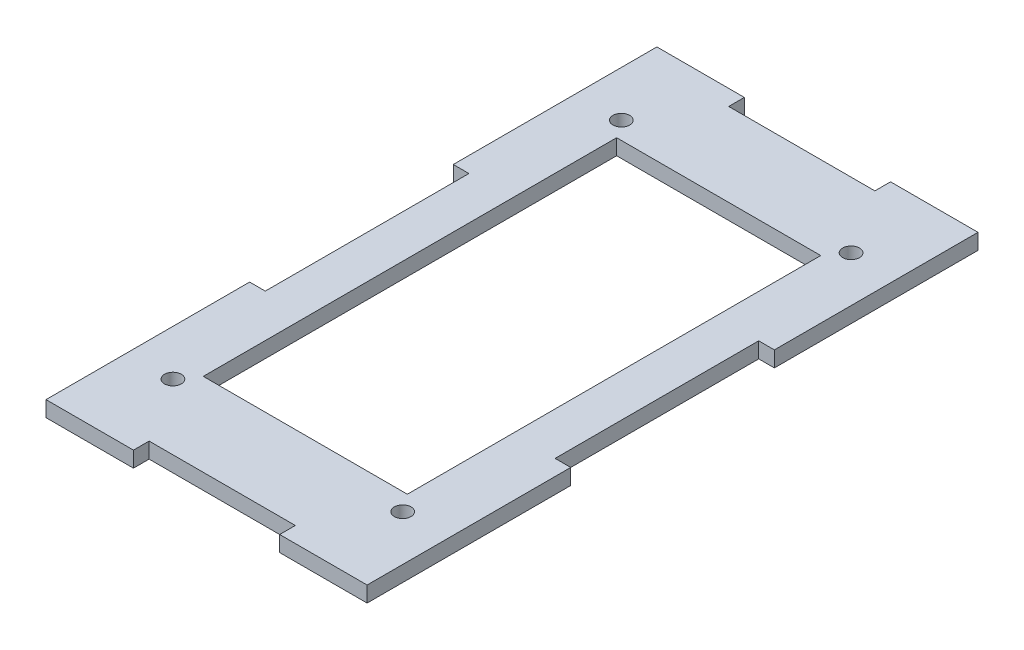
SolidWorks part; units mm, degrees
ref_plane "Front Plane" through (0, 0, 0) normal (0, 0, 1) x (1, 0, 0)
ref_plane "Top Plane" through (0, 0, 0) normal (0, 1, 0) x (1, 0, 0)
ref_plane "Right Plane" through (0, 0, 0) normal (1, 0, 0) x (0, 0, -1)
sketch "Sketch1" plane through (0, 0, 0) normal (0, 1, 0) x (1, 0, 0)
  line L0 (-30.75, 58.5) -> (-30.75, 19.5)
  line L1 (-30.75, -58.5) -> (30.75, -58.5) construction
  line L2 (-30.75, -58.5) -> (-30.75, 58.5) construction
  line L3 (-30.75, 58.5) -> (30.75, 58.5) construction
  line L4 (30.75, -58.5) -> (30.75, 58.5) construction
  line L5 (-30.75, -58.5) -> (30.75, 58.5) construction
  line L6 (-30.75, 58.5) -> (30.75, -58.5) construction
  line L7 (-27.75, -55.5) -> (27.75, -55.5) construction
  line L8 (-27.75, -55.5) -> (-27.75, 55.5) construction
  line L9 (-27.75, 55.5) -> (27.75, 55.5) construction
  line L10 (27.75, -55.5) -> (27.75, 55.5) construction
  line L11 (-27.75, -55.5) -> (27.75, 55.5) construction
  line L12 (-27.75, 55.5) -> (27.75, -55.5) construction
  line L13 (-30.75, 19.5) -> (-27.75, 19.5)
  line L14 (-27.75, 19.5) -> (-27.75, -19.5)
  line L15 (-27.75, -19.5) -> (-30.75, -19.5)
  line L16 (-30.75, -19.5) -> (-30.75, -58.5)
  line L17 (-30.75, -58.5) -> (-14, -58.5)
  line L18 (-14, -58.5) -> (-14, -55.5)
  line L19 (-14, -55.5) -> (14, -55.5)
  line L20 (14, -55.5) -> (14, -58.5)
  line L21 (14, -58.5) -> (30.75, -58.5)
  line L22 (30.75, -58.5) -> (30.75, -19.5)
  line L23 (30.75, -19.5) -> (27.75, -19.5)
  line L24 (27.75, -19.5) -> (27.75, 19.5)
  line L25 (27.75, 19.5) -> (30.75, 19.5)
  line L26 (30.75, 19.5) -> (30.75, 58.5)
  line L27 (30.75, 58.5) -> (14, 58.5)
  line L28 (14, 58.5) -> (14, 55.5)
  line L29 (14, 55.5) -> (-14, 55.5)
  line L30 (-14, 55.5) -> (-14, 58.5)
  line L31 (-14, 58.5) -> (-30.75, 58.5)
  line L33 (-22, 42.94) -> (22, 42.94) construction
  line L34 (22, 42.94) -> (22, -42.94) construction
  circle A2 centre (-22, -42.94) radius 1.6092
  circle A3 centre (22, -42.94) radius 1.6092
  circle A4 centre (22, 42.94) radius 1.6092
  circle A5 centre (-22, 42.94) radius 1.6092
  point P0 (0, 0)
  point P6 (0, 0)
  point P40 (22, 0)
  dimension "D1" = 61.5
  dimension "D2" = 117
  dimension "D3" = 3
  dimension "D4" = 3
  dimension "D7" = 44
  dimension "D8" = 85.88
  dimension "D9" = 28
extrude "Boss-Extrude1" add sketch "Sketch1" along normal blind 3
sketch "Sketch2" plane through (0, 3, 0) normal (0, 1, 0) x (1, 0, 0)
  line L0 (-0.495, 0.495) -> (0.495, -0.495) construction
  line L1 (0.495, 0.495) -> (19.545, 0.495) construction
  line L2 (0.495, 0.495) -> (0.495, 19.545) construction
  line L3 (0.495, 19.545) -> (19.545, 19.545) construction
  line L4 (19.545, 0.495) -> (19.545, 19.545) construction
  line L5 (0.495, 0.495) -> (19.545, 19.545) construction
  line L6 (0.495, 19.545) -> (19.545, 0.495) construction
  line L7 (-19.545, 0.495) -> (-0.495, 0.495) construction
  line L8 (-19.545, 0.495) -> (-19.545, 19.545) construction
  line L9 (-19.545, 19.545) -> (-0.495, 19.545) construction
  line L10 (-0.495, 0.495) -> (-0.495, 19.545) construction
  line L11 (-19.545, 0.495) -> (-0.495, 19.545) construction
  line L12 (-19.545, 19.545) -> (-0.495, 0.495) construction
  line L13 (-19.545, -19.545) -> (-0.495, -19.545) construction
  line L14 (-19.545, -19.545) -> (-19.545, -0.495) construction
  line L15 (-19.545, -0.495) -> (-0.495, -0.495) construction
  line L16 (-0.495, -19.545) -> (-0.495, -0.495) construction
  line L17 (-19.545, -19.545) -> (-0.495, -0.495) construction
  line L18 (-19.545, -0.495) -> (-0.495, -19.545) construction
  line L19 (0.495, -19.545) -> (19.545, -19.545) construction
  line L20 (0.495, -19.545) -> (0.495, -0.495) construction
  line L21 (0.495, -0.495) -> (19.545, -0.495) construction
  line L22 (19.545, -19.545) -> (19.545, -0.495) construction
  line L23 (0.495, -19.545) -> (19.545, -0.495) construction
  line L24 (0.495, -0.495) -> (19.545, -19.545) construction
  line L25 (-19.545, 20.535) -> (-0.495, 20.535) construction
  line L26 (-19.545, 20.535) -> (-19.545, 39.585) construction
  line L27 (-19.545, 39.585) -> (-0.495, 39.585) construction
  line L28 (-0.495, 20.535) -> (-0.495, 39.585) construction
  line L29 (-19.545, 20.535) -> (-0.495, 39.585) construction
  line L30 (-19.545, 39.585) -> (-0.495, 20.535) construction
  line L31 (0.495, 20.535) -> (19.545, 20.535) construction
  line L32 (0.495, 20.535) -> (0.495, 39.585) construction
  line L33 (0.495, 39.585) -> (19.545, 39.585) construction
  line L34 (19.545, 20.535) -> (19.545, 39.585) construction
  line L35 (0.495, 20.535) -> (19.545, 39.585) construction
  line L36 (0.495, 39.585) -> (19.545, 20.535) construction
  line L37 (-19.545, -39.585) -> (-0.495, -39.585) construction
  line L38 (-19.545, -39.585) -> (-19.545, -20.535) construction
  line L39 (-19.545, -20.535) -> (-0.495, -20.535) construction
  line L40 (-0.495, -39.585) -> (-0.495, -20.535) construction
  line L41 (-19.545, -39.585) -> (-0.495, -20.535) construction
  line L42 (-19.545, -20.535) -> (-0.495, -39.585) construction
  line L43 (0.495, -39.585) -> (19.545, -39.585) construction
  line L44 (0.495, -39.585) -> (0.495, -20.535) construction
  line L45 (0.495, -20.535) -> (19.545, -20.535) construction
  line L46 (19.545, -39.585) -> (19.545, -20.535) construction
  line L47 (0.495, -39.585) -> (19.545, -20.535) construction
  line L48 (0.495, -20.535) -> (19.545, -39.585) construction
  line L49 (0.495, 0.495) -> (-0.495, -0.495) construction
  line L50 (-14, -55.5) -> (14, -55.5) construction
  line L51 (-27.75, 19.5) -> (-27.75, -19.5) construction
  line L53 (-19.545, 39.585) -> (19.545, 39.585)
  line L54 (-19.545, 39.585) -> (-19.545, -39.585)
  line L55 (-19.545, -39.585) -> (19.545, -39.585)
  line L56 (19.545, 39.585) -> (19.545, -39.585)
  point P0 (10.02, 10.02)
  point P5 (-10.02, 10.02)
  point P10 (-10.02, -10.02)
  point P15 (10.02, -10.02)
  point P20 (-10.02, 30.06)
  point P25 (10.02, 30.06)
  point P30 (-10.02, -30.06)
  point P35 (10.02, -30.06)
  point P41 (0, 0)
  point P44 (0, -55.5)
  point P46 (0, 0)
  point P49 (-27.75, 0)
  dimension "D1" = 19.05
  dimension "D2" = 20.04
  dimension "D3" = 20.04
  dimension "D4" = 20.04
  dimension "D5" = 20.04
extrude "Cut-Extrude1" cut sketch "Sketch2" against normal through all
